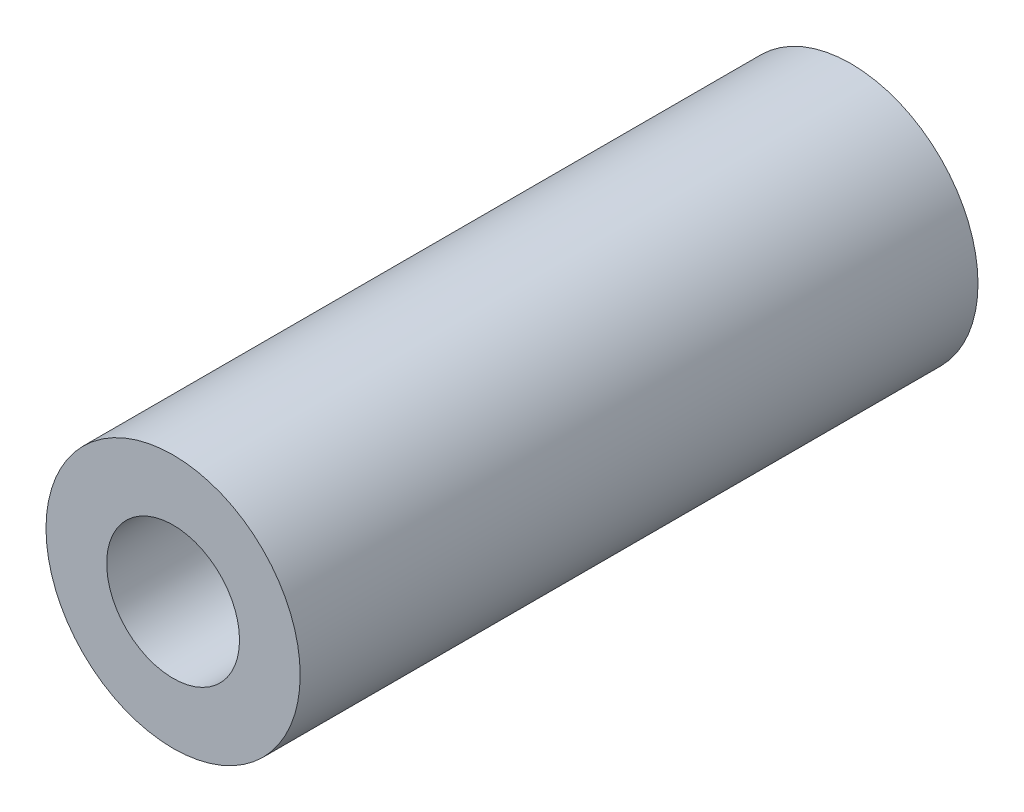
SolidWorks part; units mm, degrees
material "6061-T6 (SS)"
ref_plane "Front Plane" through (0, 0, 0) normal (0, 0, 1) x (1, 0, 0)
ref_plane "Top Plane" through (0, 0, 0) normal (0, 1, 0) x (1, 0, 0)
ref_plane "Right Plane" through (0, 0, 0) normal (1, 0, 0) x (0, 0, -1)
sketch "Sketch1" plane through (0, 0, 0) normal (0, 0, 1) x (1, 0, 0)
  circle A0 centre (0, 0) radius 4.7625
  circle A1 centre (0, 0) radius 2.4892
  dimension "D1" = 4.9784
  dimension "D2" = 9.525
extrude "Boss-Extrude1" add sketch "Sketch1" along normal mid plane 25.4
